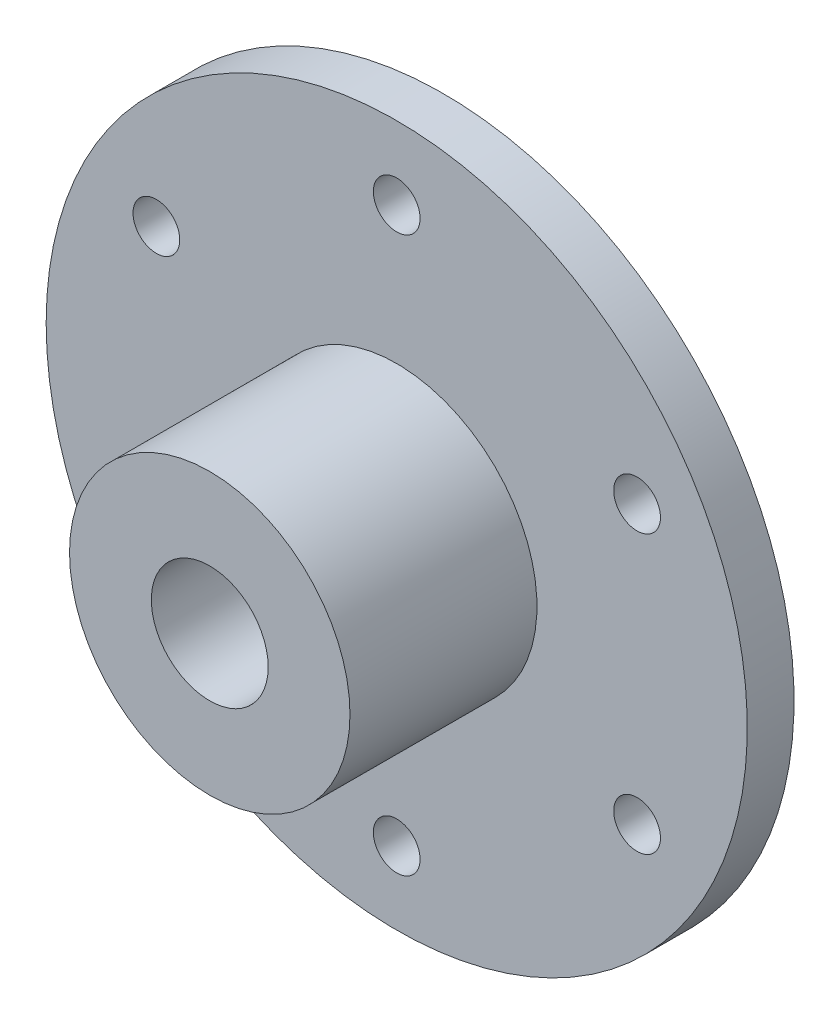
SolidWorks part; units mm, degrees
ref_plane "Front Plane" through (0, 0, 0) normal (0, 0, 1) x (1, 0, 0)
ref_plane "Top Plane" through (0, 0, 0) normal (0, 1, 0) x (1, 0, 0)
ref_plane "Right Plane" through (0, 0, 0) normal (1, 0, 0) x (0, 0, -1)
sketch "Sketch1" plane through (0, 0, 0) normal (0, 0, 1) x (1, 0, 0)
  circle A0 centre (0, 0) radius 30
extrude "Boss-Extrude1" add sketch "Sketch1" against normal blind 4
sketch "Sketch2" plane through (0, 0, 0) normal (0, 0, 1) x (1, 0, 0)
  circle A0 centre (0, 0) radius 12
extrude "Boss-Extrude2" add sketch "Sketch2" along normal blind 16
hole_wizard "Ø4.0 (4) Diameter Hole1" positions "Sketch4" profile "Sketch3" hole size "Ø4.0" standard "ANSI Metric"
sketch "Sketch4" plane through (0, 0, 0) normal (0, 0, 1) x (1, 0, 0)
  point P0 (20.5681, -11.875)
  point P1 (0, 23.75)
  point P2 (0, -23.75)
  point P3 (20.5681, 11.875)
  point P4 (-20.5681, 11.875)
  point P5 (-20.5681, -11.875)
sketch "Sketch3" plane through (20.5681, -11.875, 0) normal (1, 0, 0) x (0, -1, 0)
  line L0 (0, 0) -> (0, 4)
  line L1 (0, 4) -> (2, 4)
  line L2 (2, 4) -> (2, 0)
  line L5 (2, 0) -> (0, 0)
  line L11 (0, -6.35) -> (0, 107.95) construction
  dimension "Thru Hole Dia." = 4
  dimension "Thru Hole Depth" = 4
hole_wizard "Ø10.0 (10) Diameter Hole1" positions "Sketch6" profile "Sketch5" hole size "Ø10.0" standard "ANSI Metric"
sketch "Sketch6" plane through (0, 0, 16) normal (0, 0, 1) x (1, 0, 0)
  point P0 (0, 0)
sketch "Sketch5" plane through (0, 0, 16) normal (1, 0, 0) x (0, -1, 0)
  line L0 (0, 0) -> (0, 20)
  line L1 (0, 20) -> (5, 20)
  line L2 (5, 20) -> (5, 0)
  line L5 (5, 0) -> (0, 0)
  line L11 (0, -6.35) -> (0, 107.95) construction
  dimension "Thru Hole Dia." = 10
  dimension "Thru Hole Depth" = 20
ref_plane "Plane1" through (0, -4.5826, 0) normal (0, 1, 0) x (1, 0, 0)
hole_wizard "Ø4.0 (4) Diameter Hole2" positions "Sketch8" profile "Sketch7" hole size "Ø4.0" standard "ANSI Metric"
sketch "Sketch8" plane through (0, -4.5826, 0) normal (0, 1, 0) x (1, 0, 0)
  point P0 (0, -8)
sketch "Sketch7" plane through (0, -4.5826, 8) normal (1, 0, 0) x (0, 0, 1)
  line L0 (0, 0) -> (0, 24)
  line L1 (0, 24) -> (2, 24)
  line L2 (2, 24) -> (2, 0)
  line L5 (2, 0) -> (0, 0)
  line L10 (0, 24) -> (-2, 24) construction
  line L11 (0, -6.35) -> (0, 107.95) construction
  dimension "Hole Dia." = 4
  dimension "Hole Depth" = 24
  dimension "Drill Angle" = 180
